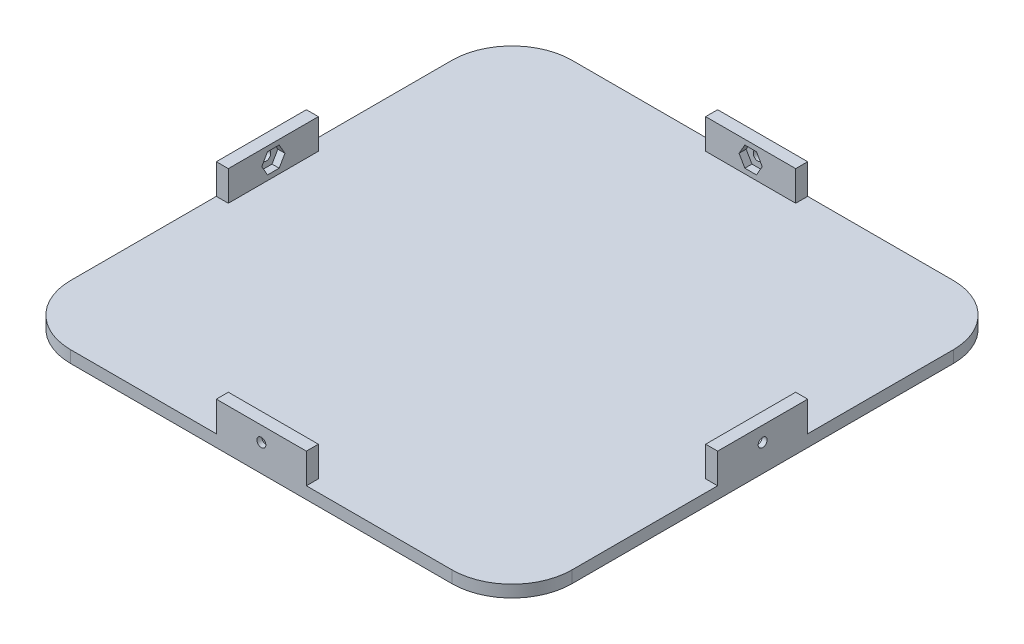
SolidWorks part; units mm, degrees
ref_plane "Plan de face" through (0, 0, 0) normal (0, 0, 1) x (1, 0, 0)
ref_plane "Plan de dessus" through (0, 0, 0) normal (0, 1, 0) x (1, 0, 0)
ref_plane "Plan de droite" through (0, 0, 0) normal (1, 0, 0) x (0, 0, -1)
sketch "Esquisse1" plane through (0, 0, 0) normal (0, 1, 0) x (1, 0, 0)
  line L0 (-19.05, 106.045) -> (19.05, 106.045) construction
  line L1 (106.045, 106.045) -> (-106.045, 106.045)
  line L2 (106.045, 106.045) -> (106.045, -106.045)
  line L3 (106.045, -106.045) -> (-106.045, -106.045)
  line L4 (-106.045, 106.045) -> (-106.045, -106.045)
  line L5 (106.045, 106.045) -> (-106.045, -106.045) construction
  line L6 (106.045, -106.045) -> (-106.045, 106.045) construction
  point P0 (0, 0)
extrude "Boss.-Extru.1" add sketch "Esquisse1" along normal blind 5.08
sketch "Esquisse2" plane through (0, 5.08, 0) normal (0, 1, 0) x (1, 0, 0)
  line L1 (-19.05, -100.965) -> (19.05, -100.965)
  line L2 (-19.05, -100.965) -> (-19.05, -106.045)
  line L3 (-19.05, -106.045) -> (19.05, -106.045)
  line L4 (19.05, -100.965) -> (19.05, -106.045)
  line L6 (-100.965, 19.05) -> (-106.045, 19.05)
  line L7 (-100.965, 19.05) -> (-100.965, -19.05)
  line L8 (-100.965, -19.05) -> (-106.045, -19.05)
  line L9 (-106.045, 19.05) -> (-106.045, -19.05)
  line L11 (19.05, 100.965) -> (-19.05, 100.965)
  line L12 (19.05, 100.965) -> (19.05, 106.045)
  line L13 (19.05, 106.045) -> (-19.05, 106.045)
  line L14 (-19.05, 100.965) -> (-19.05, 106.045)
  line L16 (100.965, -19.05) -> (106.045, -19.05)
  line L17 (100.965, -19.05) -> (100.965, 19.05)
  line L18 (100.965, 19.05) -> (106.045, 19.05)
  line L19 (106.045, -19.05) -> (106.045, 19.05)
  line L20 (-9.779, 0) -> (9.779, 0) construction
  line L21 (0, -9.779) -> (0, 9.779) construction
  line L22 (106.045, -106.045) -> (106.045, 106.045) construction
  line L23 (106.045, 106.045) -> (-106.045, 106.045) construction
  line L24 (-106.045, 106.045) -> (-106.045, -106.045) construction
  line L25 (-106.045, -106.045) -> (106.045, -106.045) construction
  point P24 (106.045, 0)
  point P27 (0, -106.045)
  point P30 (-106.045, 0)
  point P31 (0, 106.045)
  dimension "D1" = 38.1
  dimension "D2" = 5.08
extrude "Boss.-Extru.2" add sketch "Esquisse2" along normal blind 12.7
fillet "Congé1" radius 25.4 4 edges at (-106.045, 2.54, 106.045) (106.045, 2.54, 106.045) (106.045, 2.54, -106.045) (-106.045, 2.54, -106.045)
hole_wizard "Dégagement #61" positions "Esquisse3" profile "Esquisse4" hole size "#6" standard "Ansi Inch" end condition through all
sketch "Esquisse3" plane through (0, 0, 106.045) normal (0, 0, 1) x (1, 0, 0)
  line L0 (19.05, 17.78) -> (19.05, 5.08) construction
  line L1 (-19.05, 17.78) -> (19.05, 17.78) construction
  point P0 (0, 11.43)
  point P9 (19.05, 11.43)
  point P12 (0, 17.78)
sketch "Esquisse4" plane through (0, 11.43, 106.045) normal (1, 0, 0) x (0, -1, 0)
  line L0 (0, 0) -> (0, 212.09)
  line L1 (0, 212.09) -> (1.8986, 212.09)
  line L2 (1.8986, 212.09) -> (1.8986, 0)
  line L5 (1.8986, 0) -> (0, 0)
  line L11 (0, -6.35) -> (0, 107.95) construction
  dimension "Diamètre du perçage jusqu'au prochain" = 3.7973
  dimension "Profondeur du perçage jusqu'au prochain" = 212.09
sketch "Esquisse5" plane through (0, 0, -100.965) normal (0, 0, 1) x (1, 0, 0)
  line L0 (-19.05, 17.78) -> (19.05, 17.78) construction
  line L1 (2.4537, 15.68) -> (-2.4537, 15.68)
  line L2 (-2.4537, 15.68) -> (-4.9075, 11.43)
  line L3 (-4.9075, 11.43) -> (-2.4537, 7.18)
  line L4 (-2.4537, 7.18) -> (2.4537, 7.18)
  line L5 (2.4537, 7.18) -> (4.9075, 11.43)
  line L6 (4.9075, 11.43) -> (2.4537, 15.68)
  circle A0 centre (0, 11.43) radius 4.25 construction
  dimension "D1" = 8.5
extrude "Enlèv. mat.-Extru.1" cut sketch "Esquisse5" against normal blind 3
pattern_circular "Répétition circulaire1" count 4 over 360 about axis through (0, 0, 0) along (0, 1, 0) of "Dégagement #61", "Enlèv. mat.-Extru.1"
